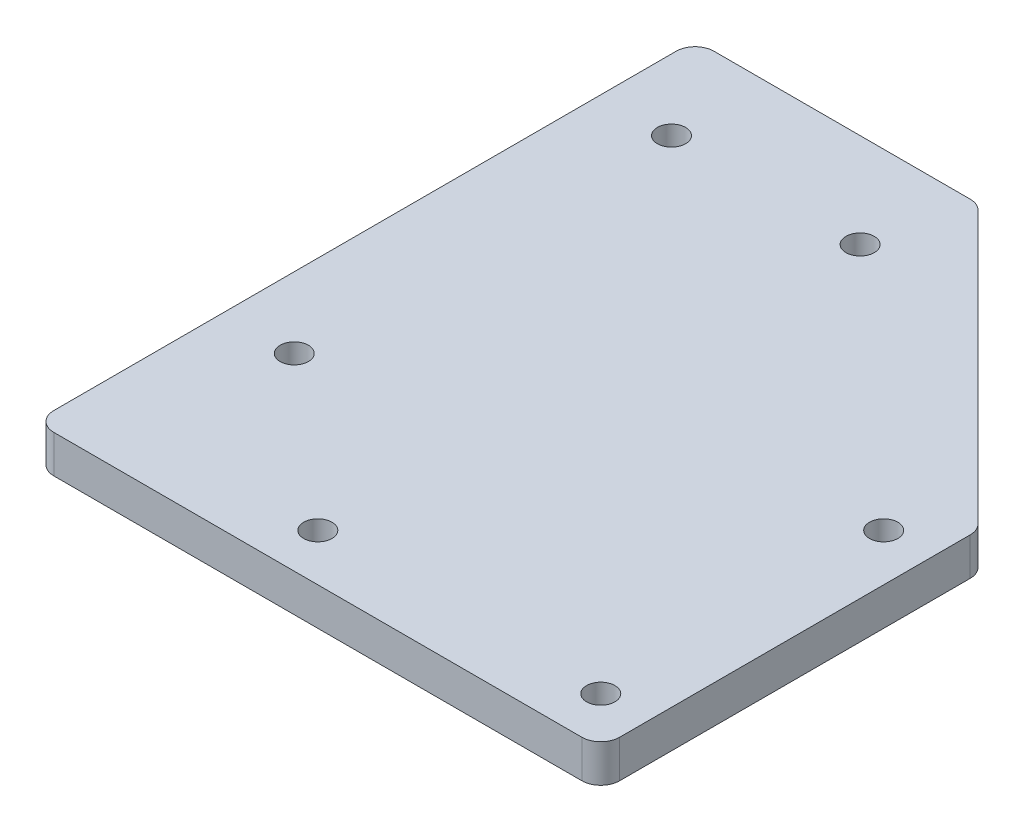
SolidWorks part; units mm, degrees
ref_plane "前视基准面" through (0, 0, 0) normal (0, 0, 1) x (1, 0, 0)
ref_plane "上视基准面" through (0, 0, 0) normal (0, 1, 0) x (1, 0, 0)
ref_plane "右视基准面" through (0, 0, 0) normal (1, 0, 0) x (0, 0, -1)
sketch "草图1" plane through (0, 0, 0) normal (0, 1, 0) x (1, 0, 0)
  line L0 (0, 0) -> (60, 0)
  line L1 (60, 0) -> (60, 40)
  line L2 (60, 40) -> (30, 70)
  line L3 (30, 70) -> (0, 70)
  line L4 (0, 70) -> (0, 0)
  dimension "D1" = 60
  dimension "D2" = 40
  dimension "D3" = 70
  dimension "D4" = 135
extrude "凸台-拉伸1" add sketch "草图1" along normal blind 4
sketch "草图2" plane through (0, 4, 0) normal (0, 1, 0) x (1, 0, 0)
  line L0 (0, 0) -> (60, 0) construction
  line L1 (0, 70) -> (0, 0) construction
  circle A0 centre (7.5, 20) radius 1.5
  circle A1 centre (7.5, 60) radius 1.5
  dimension "D1" = 20
  dimension "D2" = 40
  dimension "D3" = 7.5
extrude "切除-拉伸1" cut sketch "草图2" against normal blind 4
fillet "圆角1" radius 2 5 edges at (0, 2, -70) (30, 2, -70) (60, 2, -40) (60, 2, 0) (0, 2, 0)
sketch "草图3" plane through (0, 4, 0) normal (0, 1, 0) x (1, 0, 0)
  line L0 (60, 2) -> (60, 39.1716) construction
  line L1 (2, 0) -> (58, 0) construction
  circle A0 centre (55, 5) radius 1.5
  dimension "D1" = 5
  dimension "D2" = 5
extrude "切除-拉伸2" cut sketch "草图3" against normal blind 4
sketch "草图4" plane through (0, 4, 0) normal (0, 1, 0) x (1, 0, 0)
  circle A0 centre (27.5, 60) radius 1.5
  circle A1 centre (7.5, 60) radius 1.5 construction
  dimension "D1" = 20
extrude "切除-拉伸3" cut sketch "草图4" against normal blind 4
sketch "草图5" plane through (0, 4, 0) normal (0, 1, 0) x (1, 0, 0)
  circle A0 centre (25, 5) radius 1.5
  circle A1 centre (55, 5) radius 1.5 construction
  dimension "D1" = 30
extrude "切除-拉伸4" cut sketch "草图5" against normal blind 4
sketch "草图6" plane through (0, 4, 0) normal (0, 1, 0) x (1, 0, 0)
  circle A0 centre (55, 35) radius 1.5
  circle A1 centre (55, 5) radius 1.5 construction
  dimension "D1" = 30
extrude "切除-拉伸5" cut sketch "草图6" against normal blind 4
